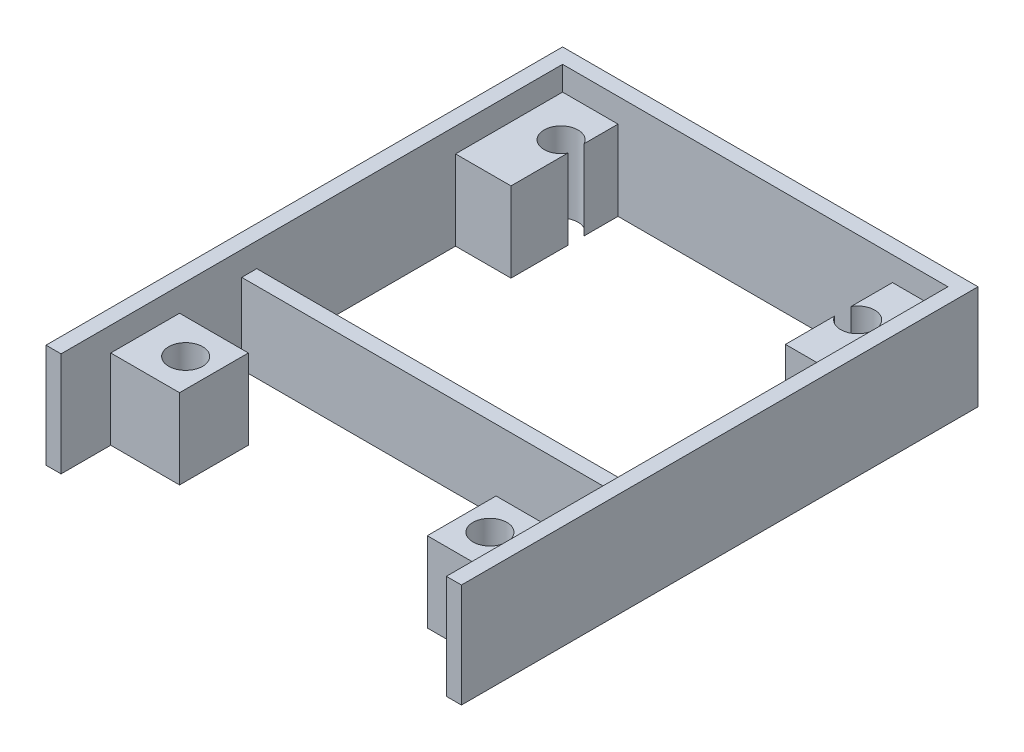
SolidWorks part; units mm, degrees
ref_plane "Front Plane" through (0, 0, 0) normal (0, 0, 1) x (1, 0, 0)
ref_plane "Top Plane" through (0, 0, 0) normal (0, 1, 0) x (1, 0, 0)
ref_plane "Right Plane" through (0, 0, 0) normal (1, 0, 0) x (0, 0, -1)
sketch "Sketch1" plane through (0, 0, 0) normal (0, 1, 0) x (1, 0, 0)
  line L0 (-10.9278, 9.0337) -> (16.6754, 9.0337)
  line L1 (-9.9278, 8.0337) -> (15.6754, 8.0337)
  line L2 (-9.9278, 8.0337) -> (-9.9278, -25.2911)
  line L3 (-9.9278, -25.2911) -> (15.6754, -25.2911)
  line L4 (15.6754, 8.0337) -> (15.6754, -25.2911)
  line L5 (16.6754, 9.0337) -> (16.6754, -26.2911)
  line L6 (-10.9278, -26.2911) -> (16.6754, -26.2911)
  line L7 (-10.9278, 9.0337) -> (-10.9278, -26.2911)
  dimension "D1" = 25.6032
  dimension "D2" = 33.3248
  dimension "D3" = 1
extrude "mainCasing" add sketch "Sketch1" against normal blind 12.93
sketch "Sketch2" plane through (0, -12.93, 0) normal (0, -1, 0) x (1, 0, 0)
  line L0 (-10.9278, -9.0337) -> (-10.9278, 26.2911) construction
  line L1 (-10.9278, 13.3912) -> (-17.2778, 13.3912)
  line L2 (-10.9278, 13.3912) -> (-10.9278, 3.8662)
  line L3 (-10.9278, 3.8662) -> (-17.2778, 3.8662)
  line L4 (-17.2778, 13.3912) -> (-17.2778, 3.8662)
  line L5 (16.6754, 26.2911) -> (16.6754, -9.0337) construction
  line L6 (16.6754, 13.3912) -> (23.0254, 13.3912)
  line L7 (16.6754, 13.3912) -> (16.6754, 3.8662)
  line L8 (16.6754, 3.8662) -> (23.0254, 3.8662)
  line L9 (23.0254, 13.3912) -> (23.0254, 3.8662)
  line L10 (19.8504, 13.3912) -> (19.8504, 3.8662) construction
  line L11 (23.0254, 8.6287) -> (16.6754, 8.6287) construction
  line L12 (-17.2778, 8.6287) -> (-10.9278, 8.6287) construction
  line L13 (-14.1028, 13.3912) -> (-14.1028, 3.8662) construction
  circle A0 centre (19.8504, 8.6287) radius 1.4732
  circle A1 centre (-14.1028, 8.6287) radius 1.4732
  dimension "D7" = 2.9464
  dimension "D8" = 2.9464
  dimension "D1" = 9.525
  dimension "D2" = 6.35
  dimension "D3" = 6.35
  dimension "D4" = 9.525
  dimension "D5" = 11.8999
  dimension "D6" = 11.8999
extrude "mountingTabs" add sketch "Sketch2" against normal blind 1.5875
sketch "Sketch3" plane through (0, 0, 0) normal (0, 1, 0) x (1, 0, 0)
  line L0 (15.6754, 8.0337) -> (-9.9278, 8.0337) construction
  line L1 (-6.2448, 8.0337) -> (-9.9278, 8.0337)
  line L2 (-6.2448, 8.0337) -> (-6.2448, 0.9217)
  line L3 (-6.2448, 0.9217) -> (-9.9278, 0.9217)
  line L4 (-9.9278, 8.0337) -> (-9.9278, 0.9217)
  line L5 (-9.9278, 8.0337) -> (-9.9278, -25.2911) construction
  line L6 (15.6754, -25.2911) -> (15.6754, 8.0337) construction
  line L7 (11.9924, 8.0337) -> (15.6754, 8.0337)
  line L8 (11.9924, 8.0337) -> (11.9924, 0.9217)
  line L9 (11.9924, 0.9217) -> (15.6754, 0.9217)
  line L10 (15.6754, 8.0337) -> (15.6754, 0.9217)
  line L11 (2.8738, 8.0337) -> (2.8738, -25.2911) construction
  line L12 (-9.9278, -25.2911) -> (15.6754, -25.2911) construction
  line L13 (-9.9278, -17.4171) -> (-5.3558, -17.4171)
  line L14 (-9.9278, -17.4171) -> (-9.9278, -21.9891)
  line L15 (-9.9278, -21.9891) -> (-5.3558, -21.9891)
  line L16 (-5.3558, -17.4171) -> (-5.3558, -21.9891)
  line L17 (15.6754, -17.4171) -> (11.1034, -17.4171)
  line L18 (15.6754, -17.4171) -> (15.6754, -21.9891)
  line L19 (15.6754, -21.9891) -> (11.1034, -21.9891)
  line L20 (11.1034, -17.4171) -> (11.1034, -21.9891)
  line L21 (-9.9278, -19.7031) -> (-5.3558, -19.7031) construction
  line L22 (11.1034, -19.7031) -> (15.6754, -19.7031) construction
  circle A0 centre (-7.2354, -19.7031) radius 1.1303
  circle A1 centre (12.983, -19.7031) radius 1.1303
  dimension "D13" = 2.2606
  dimension "D14" = 2.2606
  dimension "D1" = 4.572
  dimension "D2" = 4.572
  dimension "D3" = 7.112
  dimension "D4" = 3.683
  dimension "D5" = 7.112
  dimension "D6" = 3.683
  dimension "D7" = 4.572
  dimension "D8" = 4.572
  dimension "D9" = 18.3388
  dimension "D10" = 18.3388
  dimension "D11" = 10.1092
  dimension "D12" = 10.1092
extrude "Boss-Extrude3" add sketch "Sketch3" against normal blind 12.93
sketch "Sketch4" plane through (0, 0, 0) normal (0, 1, 0) x (1, 0, 0)
  line L0 (-10.9278, -26.2911) -> (-10.9278, 9.0337)
  line L1 (-9.9278, -25.2911) -> (15.6754, -25.2911)
  line L2 (-9.9278, -25.2911) -> (-9.9278, 8.0337)
  line L3 (-9.9278, 8.0337) -> (15.6754, 8.0337)
  line L4 (15.6754, -25.2911) -> (15.6754, 8.0337)
  line L5 (-10.9278, 9.0337) -> (16.6754, 9.0337)
  line L6 (16.6754, -26.2911) -> (16.6754, 9.0337)
  line L7 (-10.9278, -26.2911) -> (16.6754, -26.2911)
  dimension "D1" = 1
extrude "Boss-Extrude4" add sketch "Sketch4" along normal blind 1.6002
sketch "Sketch5" plane through (0, -12.93, 0) normal (0, -1, 0) x (1, 0, 0)
  line L0 (2.8738, 25.2911) -> (2.8738, -8.0337) construction
  line L1 (-9.9278, 25.2911) -> (15.6754, 25.2911) construction
  line L2 (11.9924, -8.0337) -> (-6.2448, -8.0337) construction
  circle A0 centre (-7.2354, -5.2397) radius 1.1303
  circle A1 centre (12.983, -4.7317) radius 1.1303
  dimension "D1" = 2.2606
  dimension "D2" = 2.2606
  dimension "D3" = 10.1092
  dimension "D4" = 10.1092
  dimension "D5" = 2.794
  dimension "D6" = 3.302
extrude "upperHoles" cut sketch "Sketch5" against normal through all
sketch "Sketch6" plane through (0, -12.93, 0) normal (0, -1, 0) x (1, 0, 0)
  line L0 (-9.9278, -0.9217) -> (-9.9278, 17.4171) construction
  line L1 (-9.9278, 13.2863) -> (15.6754, 13.2863)
  line L2 (-9.9278, 13.2863) -> (-9.9278, 12.2863)
  line L3 (-9.9278, 12.2863) -> (15.6754, 12.2863)
  line L4 (15.6754, 13.2863) -> (15.6754, 12.2863)
  line L5 (15.6754, 17.4171) -> (15.6754, -0.9217) construction
  dimension "D1" = 1
  dimension "D2" = 20.32
extrude "Boss-Extrude5" add sketch "Sketch6" against normal up to surface (12.93 mm away) up to face at (-7.2354, 0, 20.8334)
sketch "Sketch7" plane through (0, -12.93, 0) normal (0, -1, 0) x (1, 0, 0)
  line L0 (-10.9278, 13.3912) -> (-10.9278, 26.2911) construction
  line L1 (-10.9278, 26.2911) -> (16.6754, 26.2911)
  line L2 (-10.9278, 26.2911) -> (-10.9278, 25.2911)
  line L3 (-10.9278, 25.2911) -> (16.6754, 25.2911)
  line L4 (16.6754, 26.2911) -> (16.6754, 25.2911)
  line L5 (-10.9278, 26.2911) -> (16.6754, 26.2911) construction
  line L6 (16.6754, 26.2911) -> (16.6754, 13.3912) construction
extrude "Cut-Extrude2" cut sketch "Sketch7" against normal through all
sketch "Sketch8" plane through (0, -12.93, 0) normal (0, -1, 0) x (1, 0, 0)
  line L1 (-20.9851, 26.3194) -> (26.211, 26.3194)
  line L2 (-20.9851, 26.3194) -> (-20.9851, -10.1568)
  line L3 (-20.9851, -10.1568) -> (26.211, -10.1568)
  line L4 (26.211, 26.3194) -> (26.211, -10.1568)
extrude "tempMatRemoval" cut sketch "Sketch8" against normal blind 7.62
